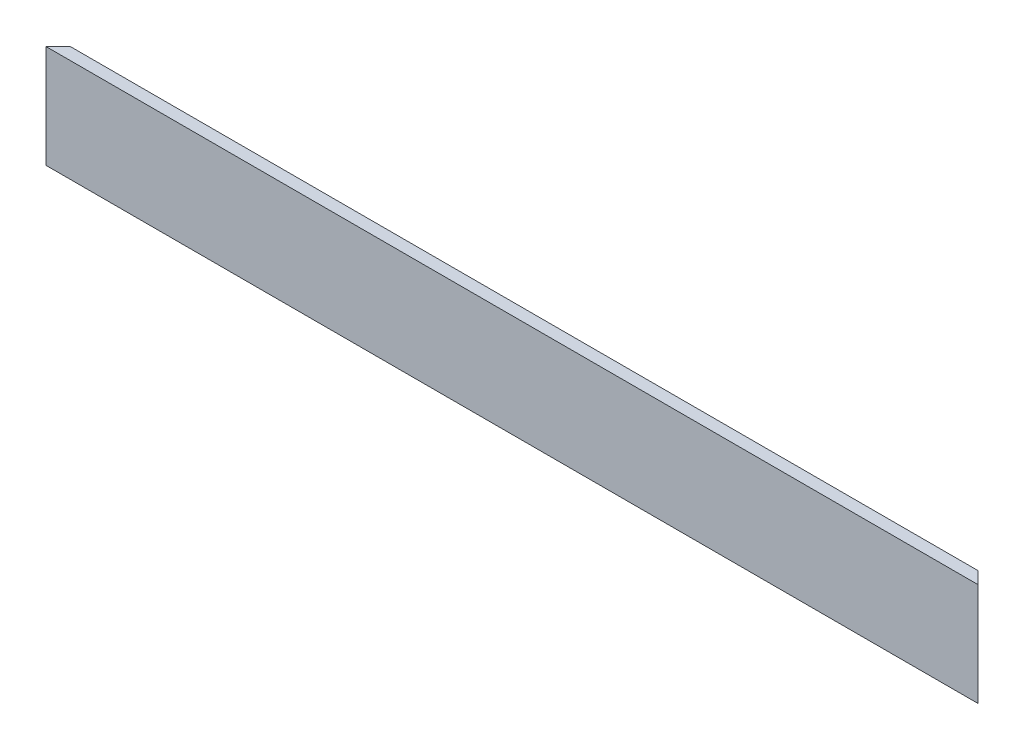
SolidWorks part; units mm, degrees
material "0.6020 (EN-GJL-200)"
ref_plane "Alzado" through (0, 0, 0) normal (0, 0, 1) x (1, 0, 0)
ref_plane "Planta" through (0, 0, 0) normal (0, 1, 0) x (1, 0, 0)
ref_plane "Vista lateral" through (0, 0, 0) normal (1, 0, 0) x (0, 0, -1)
sketch "Croquis1" plane through (0, 0, 0) normal (1, 0, 0) x (0, 0, -1)
  line L0 (-16.8743, 6.35) -> (-16.8743, -19.05)
  line L1 (-16.8743, -19.05) -> (8.5257, -19.05)
  line L2 (8.5257, -19.05) -> (8.5257, -16.05)
  line L3 (8.5257, -16.05) -> (-13.8743, -16.05)
  line L4 (-13.8743, -16.05) -> (-13.8743, 6.35)
  line L5 (-16.8743, 6.35) -> (-13.8743, 6.35)
  dimension "D1" = 25.4
  dimension "D2" = 3
  dimension "D3" = 3
  dimension "D4" = 25.4
extrude "Saliente-Extruir1" add sketch "Croquis1" along normal blind 230
sketch "Croquis2" plane through (0, 6.35, 0) normal (0, 1, 0) x (1, 0, 0)
  line L0 (0, -16.8743) -> (25.4, 8.5257)
  line L1 (230, 8.5257) -> (0, 8.5257) construction
  line L2 (25.4, 8.5257) -> (0, 8.5257)
  line L3 (0, 8.5257) -> (0, -16.8743)
  line L4 (230, -16.8743) -> (204.6, 8.5257)
  line L5 (204.6, 8.5257) -> (230, 8.5257)
  line L6 (230, 8.5257) -> (230, -16.8743)
  dimension "D1" = 45
  dimension "D2" = 45
extrude "Cortar-Extruir1" cut sketch "Croquis2" against normal blind 75
